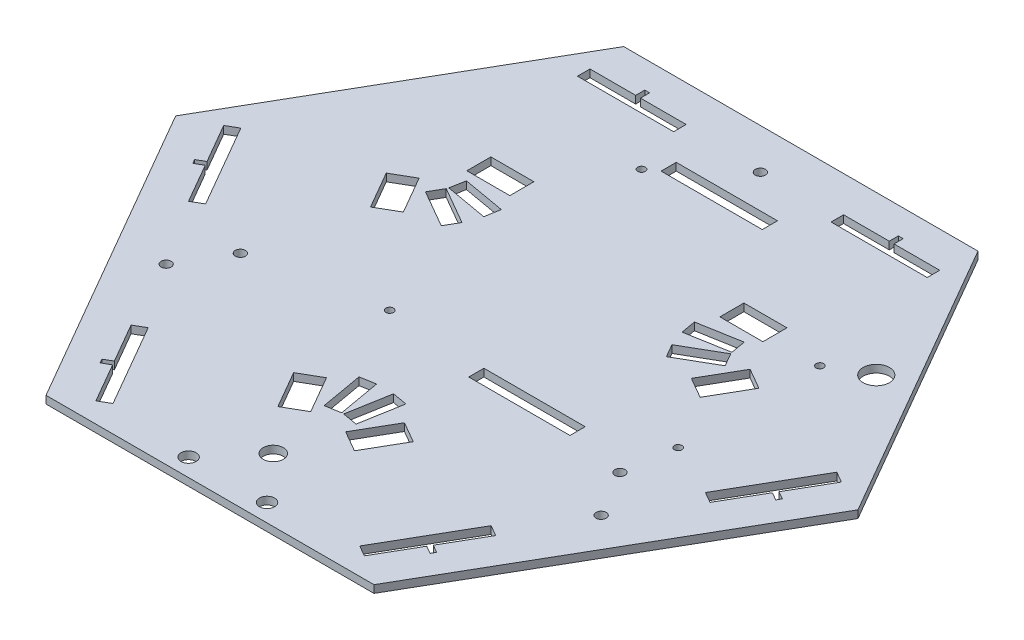
SolidWorks part; units mm, degrees
ref_plane "Front Plane" through (0, 0, 0) normal (0, 0, 1) x (1, 0, 0)
ref_plane "Top Plane" through (0, 0, 0) normal (0, 1, 0) x (1, 0, 0)
ref_plane "Right Plane" through (0, 0, 0) normal (1, 0, 0) x (0, 0, -1)
sketch "Sketch1" plane through (0, 0, 0) normal (0, 1, 0) x (1, 0, 0)
  line L0 (82.3009, -148.2643) -> (171.2009, 5.715)
  line L1 (171.2009, 5.715) -> (88.9, 148.2643)
  line L2 (88.9, 148.2643) -> (-88.9, 148.2643)
  line L3 (-88.9, 148.2643) -> (-171.2009, 5.715)
  line L4 (-171.2009, 5.715) -> (-82.3009, -148.2643)
  line L5 (-82.3009, -148.2643) -> (82.3009, -148.2643)
  line L6 (-39.37, 123.7859) -> (-39.37, 130.0724)
  line L7 (-87.63, 123.7859) -> (-87.63, 130.0724)
  line L8 (39.37, 124.0399) -> (39.37, 130.3264)
  line L9 (87.63, 124.0399) -> (87.63, 130.3264)
  line L10 (125.417, -25.0401) -> (130.8613, -28.1834)
  line L11 (149.547, 16.7543) -> (154.9913, 13.611)
  line L12 (86.047, -93.231) -> (91.4913, -96.3742)
  line L13 (61.917, -135.0253) -> (67.3613, -138.1686)
  line L14 (-61.917, -135.0253) -> (-67.3613, -138.1686)
  line L15 (-86.047, -93.231) -> (-91.4913, -96.3742)
  line L16 (-125.417, -25.0401) -> (-130.8613, -28.1834)
  line L17 (-149.547, 16.7543) -> (-154.9913, 13.611)
  line L18 (-149.547, 16.7543) -> (-125.417, -25.0401)
  line L19 (-86.047, -93.231) -> (-61.917, -135.0253)
  line L20 (61.917, -135.0253) -> (86.047, -93.231)
  line L21 (125.417, -25.0401) -> (149.547, 16.7543)
  line L22 (87.63, 124.0399) -> (39.37, 124.0399)
  line L23 (-39.37, 123.7859) -> (-87.63, 123.7859)
  line L24 (-147.489, -8.5273) -> (-146.2825, -10.617)
  line L25 (-146.2825, -10.617) -> (-142.323, -8.331)
  line L26 (-143.5295, -6.2413) -> (-147.489, -8.5273)
  line L27 (-83.989, -118.5125) -> (-82.7825, -120.6023)
  line L28 (-82.7825, -120.6023) -> (-78.823, -118.3163)
  line L29 (-80.0295, -116.2265) -> (-83.989, -118.5125)
  line L30 (-62.2935, 130.0724) -> (-62.2935, 134.6444)
  line L31 (-62.2935, 134.6444) -> (-64.7065, 134.6444)
  line L32 (-64.7065, 134.6444) -> (-64.7065, 130.0724)
  line L33 (64.7065, 134.8984) -> (62.2935, 134.8984)
  line L34 (62.2935, 134.8984) -> (62.2935, 130.3264)
  line L35 (64.7065, 130.3264) -> (64.7065, 134.8984)
  line L36 (146.2825, -10.617) -> (147.489, -8.5273)
  line L37 (147.489, -8.5273) -> (143.5295, -6.2413)
  line L38 (142.323, -8.331) -> (146.2825, -10.617)
  line L39 (78.823, -118.3163) -> (82.7825, -120.6023)
  line L40 (82.7825, -120.6023) -> (83.989, -118.5125)
  line L41 (83.989, -118.5125) -> (80.0295, -116.2265)
  line L42 (52.705, 54.9193) -> (74.295, 54.9193)
  line L43 (74.295, 54.9193) -> (74.295, 66.9843)
  line L44 (74.295, 66.9843) -> (52.705, 66.9843)
  line L45 (52.705, 66.9843) -> (52.705, 54.9193)
  line L46 (83.0592, 39.7392) -> (72.2642, 21.0417)
  line L47 (72.2642, 21.0417) -> (82.7128, 15.0092)
  line L48 (82.7128, 15.0092) -> (93.5078, 33.7067)
  line L49 (93.5078, 33.7067) -> (83.0592, 39.7392)
  line L50 (-74.295, 54.9193) -> (-52.705, 54.9193)
  line L51 (-52.705, 54.9193) -> (-52.705, 66.9843)
  line L52 (-52.705, 66.9843) -> (-74.295, 66.9843)
  line L53 (-74.295, 66.9843) -> (-74.295, 54.9193)
  line L54 (-72.2642, 21.0417) -> (-83.0592, 39.7392)
  line L55 (-83.0592, 39.7392) -> (-93.5078, 33.7067)
  line L56 (-93.5078, 33.7067) -> (-82.7128, 15.0092)
  line L57 (-82.7128, 15.0092) -> (-72.2642, 21.0417)
  line L58 (-19.5592, -70.246) -> (-30.0078, -76.2785)
  line L59 (-30.0078, -76.2785) -> (-19.2128, -94.976)
  line L60 (-19.2128, -94.976) -> (-8.7642, -88.9435)
  line L61 (19.5592, -70.246) -> (8.7642, -88.9435)
  line L62 (8.7642, -88.9435) -> (19.2128, -94.976)
  line L63 (19.2128, -94.976) -> (30.0078, -76.2785)
  line L64 (30.0078, -76.2785) -> (19.5592, -70.246)
  line L65 (-19.5592, -70.246) -> (-8.7642, -88.9435)
  line L66 (-130.8613, -28.1834) -> (-142.323, -8.331)
  line L67 (-143.5295, -6.2413) -> (-154.9913, 13.611)
  line L68 (-67.3613, -138.1686) -> (-78.823, -118.3163)
  line L69 (-80.0295, -116.2265) -> (-91.4913, -96.3742)
  line L70 (91.4913, -96.3742) -> (80.0295, -116.2265)
  line L71 (78.823, -118.3163) -> (67.3613, -138.1686)
  line L72 (154.9913, 13.611) -> (143.5295, -6.2413)
  line L73 (142.323, -8.331) -> (130.8613, -28.1834)
  line L74 (39.37, 130.3264) -> (62.2935, 130.3264)
  line L75 (64.7065, 130.3264) -> (87.63, 130.3264)
  line L76 (-87.63, 130.0724) -> (-64.7065, 130.0724)
  line L77 (-62.2935, 130.0724) -> (-39.37, 130.0724)
  line L78 (-0.508, -81.661) -> (-4.2571, -60.399)
  line L79 (-4.2571, -60.399) -> (-11.7613, -61.7222)
  line L80 (-11.7613, -61.7222) -> (-8.0122, -82.9842)
  line L81 (-8.0122, -82.9842) -> (-0.508, -81.661)
  line L82 (4.2571, -60.399) -> (0.508, -81.661)
  line L83 (0.508, -81.661) -> (8.0122, -82.9842)
  line L84 (8.0122, -82.9842) -> (11.7613, -61.7222)
  line L85 (11.7613, -61.7222) -> (4.2571, -60.399)
  line L86 (71.4675, 41.5903) -> (52.77, 30.7953)
  line L87 (52.77, 30.7953) -> (56.58, 24.1962)
  line L88 (56.58, 24.1962) -> (75.2775, 34.9912)
  line L89 (75.2775, 34.9912) -> (71.4675, 41.5903)
  line L90 (49.858, 38.7959) -> (71.12, 42.545)
  line L91 (71.12, 42.545) -> (69.7968, 50.0492)
  line L92 (69.7968, 50.0492) -> (48.5348, 46.3002)
  line L93 (48.5348, 46.3002) -> (49.858, 38.7959)
  line L94 (-71.356, 42.9525) -> (-50.094, 39.2034)
  line L95 (-50.094, 39.2034) -> (-48.7708, 46.7077)
  line L96 (-48.7708, 46.7077) -> (-70.0328, 50.4567)
  line L97 (-70.0328, 50.4567) -> (-71.356, 42.9525)
  line L98 (-53.006, 31.2028) -> (-71.7035, 41.9978)
  line L99 (-71.7035, 41.9978) -> (-75.5135, 35.3987)
  line L100 (-75.5135, 35.3987) -> (-56.816, 24.6037)
  line L101 (-56.816, 24.6037) -> (-53.006, 31.2028)
  line L102 (-25.4, 103.505) -> (25.4, 103.505)
  line L103 (25.4, 103.505) -> (25.4, 111.125)
  line L104 (25.4, 111.125) -> (-25.4, 111.125)
  line L105 (-25.4, 111.125) -> (-25.4, 103.505)
  line L106 (15.825, -34.2367) -> (66.625, -34.2367)
  line L107 (66.625, -34.2367) -> (66.625, -26.6167)
  line L108 (66.625, -26.6167) -> (15.825, -26.6167)
  line L109 (15.825, -26.6167) -> (15.825, -34.2367)
  circle A0 centre (0, -116.5143) radius 5.08
  circle A1 centre (-19.6587, -139.347) radius 3.81
  circle A2 centre (19.7113, -139.347) radius 3.81
  circle A3 centre (-95.25, -37.7743) radius 2.54
  circle A4 centre (95.25, -37.7743) radius 2.54
  circle A5 centre (-31.1137, 99.3962) radius 1.905
  circle A6 centre (-33.02, -25.0743) radius 1.905
  circle A7 centre (99.06, -12.3743) radius 1.905
  circle A8 centre (99.06, 58.7457) radius 1.905
  circle A9 centre (0, 127.9443) radius 2.54
  circle A10 centre (-109.1533, -61.1147) radius 2.54
  circle A11 centre (109.1533, -61.1147) radius 2.54
  circle A12 centre (117.2455, 68.8666) radius 6.604
  point P136 (0, 0)
  point P138 (171.2009, 5.715)
  point P139 (171.2009, 5.715)
  point P140 (171.2009, 5.715)
  point P141 (117.2455, 66.9843)
  dimension "D1" = 13.208
  dimension "D2" = 5.08
  dimension "D3" = 7.62
  dimension "D4" = 3.81
  dimension "D5" = 10.16
  dimension "D8" = 0.508
  dimension "D11" = 4.2571
  dimension "D12" = 15.825
  dimension "D13" = 25.4
  dimension "D14" = 19.7113
  dimension "D15" = 39.37
  dimension "D16" = 48.5348
  dimension "D17" = 49.858
  dimension "D18" = 52.705
  dimension "D19" = 52.77
  dimension "D20" = 56.58
  dimension "D21" = 61.917
  dimension "D22" = 62.2935
  dimension "D23" = 66.625
  dimension "D24" = 69.7968
  dimension "D25" = 72.2642
  dimension "D26" = 78.823
  dimension "D27" = 82.3009
  dimension "D28" = 82.7128
  dimension "D29" = 87.63
  dimension "D30" = 88.9
  dimension "D31" = 143.5295
  dimension "D32" = 8.7642
  dimension "D33" = 48.7708
  dimension "D34" = 52.705
  dimension "D35" = 53.006
  dimension "D36" = 83.989
  dimension "D37" = 15.0092
  dimension "D38" = 24.1962
  dimension "D39" = 24.6037
  dimension "D40" = 41.9978
  dimension "D41" = 42.9525
  dimension "D42" = 54.9193
  dimension "D43" = 103.505
  dimension "D44" = 123.7859
  dimension "D45" = 124.0399
  dimension "D46" = 95.25
  dimension "D47" = 99.06
  dimension "D48" = 109.1533
  dimension "D49" = 117.2455
  dimension "D50" = 10.617
  dimension "D51" = 34.2367
  dimension "D52" = 37.7743
  dimension "D53" = 60.399
  dimension "D54" = 61.1147
  dimension "D55" = 116.5143
  dimension "D56" = 139.347
  dimension "D66" = 19.6587
  dimension "D69" = 31.1137
  dimension "D70" = 33.02
  dimension "D99" = 95.25
  dimension "D100" = 109.1533
sketch "Sketch2" plane through (0, 0, 0) normal (0, 1, 0) x (1, 0, 0)
  line L0 (-88.9, 148.2643) -> (82.3009, -148.2643) construction
  line L1 (88.9, 148.2643) -> (-82.3009, -148.2643) construction
  line L2 (171.2009, 5.715) -> (-171.2009, 5.715) construction
  line L3 (0, 148.2643) -> (0, -148.2643) construction
  line L4 (88.9, 148.2643) -> (-88.9, 148.2643) construction
  line L5 (-82.3009, -148.2643) -> (82.3009, -148.2643) construction
  line L6 (-126.7509, -71.2747) -> (130.0504, 76.9897) construction
  line L7 (-171.2009, 5.715) -> (-82.3009, -148.2643) construction
  line L8 (171.2009, 5.715) -> (88.9, 148.2643) construction
  line L9 (-130.0504, 76.9897) -> (126.7509, -71.2747) construction
  line L10 (-88.9, 148.2643) -> (-171.2009, 5.715) construction
  line L11 (82.3009, -148.2643) -> (171.2009, 5.715) construction
  line L12 (-146.8857, -9.5722) -> (-161.9666, -18.2792) construction
  line L13 (-147.489, -8.5273) -> (-146.2825, -10.617) construction
  line L14 (-83.3857, -119.5574) -> (-98.4666, -128.2644) construction
  line L15 (-83.989, -118.5125) -> (-82.7825, -120.6023) construction
  line L16 (-161.9666, -18.2792) -> (-135.9316, -63.3731) construction
  line L17 (-98.4666, -128.2644) -> (-124.5017, -83.1704) construction
  line L18 (-165.4307, -20.2791) -> (-101.9307, -130.2644) construction
  line L19 (0, 1.905) -> (-101.9307, -130.2644) construction
  line L20 (-165.4307, -20.2791) -> (0, 1.905) construction
  line L21 (-135.9316, -63.3731) -> (-139.3957, -65.3731) construction
  line L22 (-135.9316, -63.3731) -> (-132.4675, -61.3731) construction
  line L23 (63.5033, 156.2643) -> (0, 1.905) construction
  line L24 (63.5033, 134.8504) -> (63.5033, 152.2643) construction
  line L25 (63.5033, 152.2643) -> (11.4333, 152.2643) construction
  line L26 (63.5033, 156.2643) -> (-63.4967, 156.2643) construction
  line L27 (0, 1.905) -> (-63.4967, 156.2643) construction
  line L28 (-63.4967, 134.8504) -> (-63.4967, 152.2643) construction
  line L29 (-63.4967, 152.2643) -> (-11.4266, 152.2643) construction
  line L30 (101.9274, -130.2702) -> (0, 1.905) construction
  line L31 (83.3824, -119.5632) -> (98.4633, -128.2702) construction
  line L32 (98.4633, -128.2702) -> (124.4983, -83.1762) construction
  line L33 (101.9274, -130.2702) -> (165.4274, -20.2849) construction
  line L34 (0, 1.905) -> (165.4274, -20.2849) construction
  line L35 (146.8824, -9.578) -> (161.9633, -18.2849) construction
  line L36 (161.9633, -18.2849) -> (135.9283, -63.3789) construction
  point P30 (0, 1.905)
  point P44 (-61.0168, 144.7258)
  point P46 (0, 0)
  dimension "D1" = 4
  dimension "D2" = 52.07
  dimension "D3" = 3
extrude "Boss-Extrude1" add sketch "Sketch1" along normal blind 3.81
